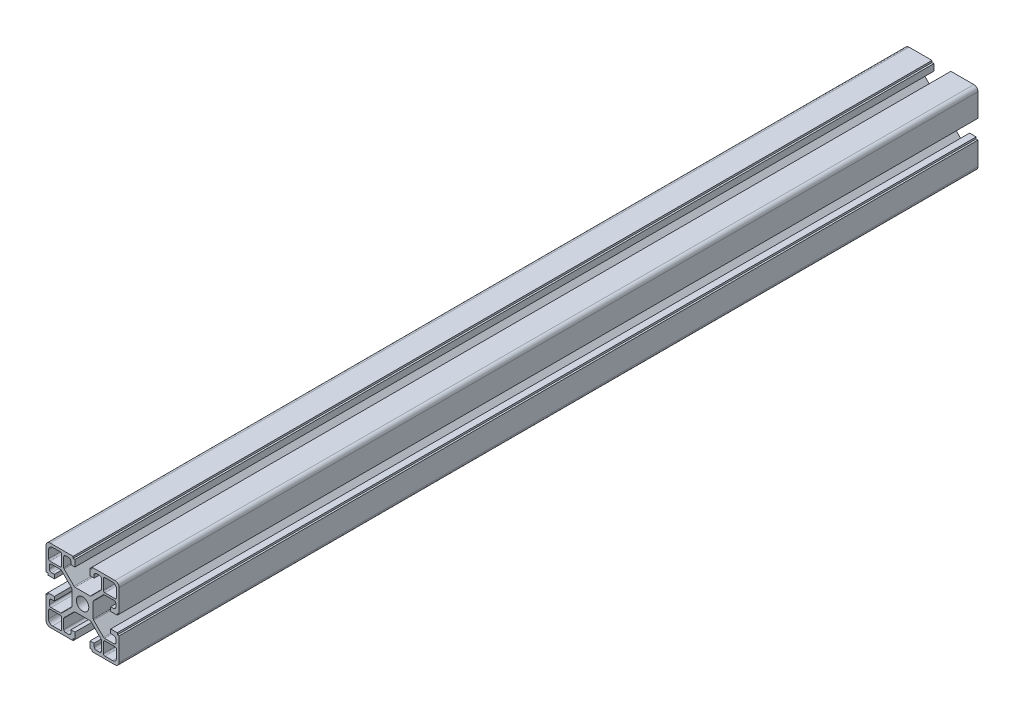
SolidWorks part; units mm, degrees
material "6063-T5"
ref_plane "Front Plane" through (0, 0, 0) normal (0, 0, 1) x (1, 0, 0)
ref_plane "Top Plane" through (0, 0, 0) normal (0, 1, 0) x (1, 0, 0)
ref_plane "Right Plane" through (0, 0, 0) normal (1, 0, 0) x (0, 0, -1)
sketch "Sketch1" plane through (0, 0, 0) normal (0, 0, 1) x (1, 0, 0)
  line L4 (20, 17.75) -> (20, 5.15)
  line L5 (0, -17.7813) -> (0, 18.2) construction
  line L6 (0, 0) -> (38.8613, 0) construction
  line L8 (18.6, 16.35) -> (18.6, 12.2)
  line L10 (11.4, 17.8) -> (11.4, 12.2)
  line L11 (-4.1, 5.85) -> (4.1, 5.85)
  line L14 (5.85, 4.1089) -> (5.85, -4.1089)
  line L17 (12.2, 11.4) -> (17.8, 11.4)
  line L24 (4.15, 19) -> (4.15, 15.4)
  line L25 (4.15, 15.4) -> (6.35, 15.4)
  line L26 (6.35, 15.4) -> (6.35, 16.95)
  line L27 (10.3, 17.2) -> (10.3, 12.0545)
  line L28 (10.0659, 11.489) -> (4.6659, 6.0845)
  line L29 (6.0841, 4.6743) -> (11.4708, 10.0655)
  line L30 (12.0367, 10.3) -> (17.2, 10.3)
  line L31 (18.2, 9.3) -> (18.2, 7.6)
  line L32 (16.95, 6.35) -> (15.4, 6.35)
  line L33 (15.4, 6.35) -> (15.4, 4.15)
  line L34 (15.4, 4.15) -> (19, 4.15)
  line L35 (18.6, 18.6) -> (18.6, -18.6) construction
  line L36 (-18.6, 18.6) -> (18.6, 18.6) construction
  line L37 (-20, 20) -> (20, 20) construction
  line L38 (20, 20) -> (20, -20) construction
  line L40 (7.6, 18.2) -> (9.3, 18.2)
  line L42 (4.15, 19) -> (5.15, 19)
  line L43 (5.15, 19) -> (5.15, 20)
  line L56 (-18.6, 18.6) -> (-18.6, -18.6) construction
  line L57 (-20, 20) -> (-20, -20) construction
  line L60 (5.15, 20) -> (17.75, 20)
  line L91 (-18.6, -18.6) -> (18.6, -18.6) construction
  line L92 (-20, -20) -> (20, -20) construction
  line L93 (12.2, 18.6) -> (16.35, 18.6)
  line L94 (17.9399, 17.9421) -> (20, 20) construction
  line L95 (0, 0) -> (11.4, 11.4094) construction
  line L101 (19, 4.15) -> (19, 5.15)
  line L102 (19, 5.15) -> (20, 5.15)
  line L104 (-5.85, 4.1089) -> (-5.85, -4.1089)
  line L105 (-19, 5.15) -> (-20, 5.15)
  line L106 (-19, 4.15) -> (-19, 5.15)
  line L107 (-12.2, 18.6) -> (-16.35, 18.6)
  line L108 (-5.15, 20) -> (-17.75, 20)
  line L109 (-5.15, 19) -> (-5.15, 20)
  line L110 (-4.15, 19) -> (-5.15, 19)
  line L111 (-7.6, 18.2) -> (-9.3, 18.2)
  line L112 (-15.4, 4.15) -> (-19, 4.15)
  line L113 (-15.4, 6.35) -> (-15.4, 4.15)
  line L114 (-16.95, 6.35) -> (-15.4, 6.35)
  line L115 (-18.2, 9.3) -> (-18.2, 7.6)
  line L116 (-12.0367, 10.3) -> (-17.2, 10.3)
  line L117 (-6.0841, 4.6743) -> (-11.4708, 10.0655)
  line L118 (-10.0659, 11.489) -> (-4.6659, 6.0845)
  line L119 (-10.3, 17.2) -> (-10.3, 12.0545)
  line L120 (-6.35, 15.4) -> (-6.35, 16.95)
  line L121 (-4.15, 15.4) -> (-6.35, 15.4)
  line L122 (-4.15, 19) -> (-4.15, 15.4)
  line L123 (-12.2, 11.4) -> (-17.8, 11.4)
  line L124 (-11.4, 17.8) -> (-11.4, 12.2)
  line L125 (-18.6, 16.35) -> (-18.6, 12.2)
  line L126 (-20, 17.75) -> (-20, 5.15)
  line L127 (-20, -17.75) -> (-20, -5.15)
  line L128 (-18.6, -16.35) -> (-18.6, -12.2)
  line L129 (-11.4, -17.8) -> (-11.4, -12.2)
  line L130 (-12.2, -11.4) -> (-17.8, -11.4)
  line L131 (-4.15, -19) -> (-4.15, -15.4)
  line L132 (-4.15, -15.4) -> (-6.35, -15.4)
  line L133 (-6.35, -15.4) -> (-6.35, -16.95)
  line L134 (-10.3, -17.2) -> (-10.3, -12.0545)
  line L135 (-10.0659, -11.489) -> (-4.6659, -6.0845)
  line L136 (-6.0841, -4.6743) -> (-11.4708, -10.0655)
  line L137 (-12.0367, -10.3) -> (-17.2, -10.3)
  line L138 (-18.2, -9.3) -> (-18.2, -7.6)
  line L139 (-16.95, -6.35) -> (-15.4, -6.35)
  line L140 (-15.4, -6.35) -> (-15.4, -4.15)
  line L141 (-15.4, -4.15) -> (-19, -4.15)
  line L142 (-7.6, -18.2) -> (-9.3, -18.2)
  line L143 (-4.15, -19) -> (-5.15, -19)
  line L144 (-5.15, -19) -> (-5.15, -20)
  line L145 (-5.15, -20) -> (-17.75, -20)
  line L146 (-12.2, -18.6) -> (-16.35, -18.6)
  line L147 (-19, -4.15) -> (-19, -5.15)
  line L148 (-19, -5.15) -> (-20, -5.15)
  line L149 (19, -5.15) -> (20, -5.15)
  line L150 (19, -4.15) -> (19, -5.15)
  line L151 (12.2, -18.6) -> (16.35, -18.6)
  line L152 (5.15, -20) -> (17.75, -20)
  line L153 (5.15, -19) -> (5.15, -20)
  line L154 (4.15, -19) -> (5.15, -19)
  line L155 (7.6, -18.2) -> (9.3, -18.2)
  line L156 (15.4, -4.15) -> (19, -4.15)
  line L157 (15.4, -6.35) -> (15.4, -4.15)
  line L158 (16.95, -6.35) -> (15.4, -6.35)
  line L159 (18.2, -9.3) -> (18.2, -7.6)
  line L160 (12.0367, -10.3) -> (17.2, -10.3)
  line L161 (6.0841, -4.6743) -> (11.4708, -10.0655)
  line L162 (10.0659, -11.489) -> (4.6659, -6.0845)
  line L163 (10.3, -17.2) -> (10.3, -12.0545)
  line L164 (6.35, -15.4) -> (6.35, -16.95)
  line L165 (4.15, -15.4) -> (6.35, -15.4)
  line L166 (4.15, -19) -> (4.15, -15.4)
  line L167 (12.2, -11.4) -> (17.8, -11.4)
  line L168 (-4.1, -5.85) -> (4.1, -5.85)
  line L169 (11.4, -17.8) -> (11.4, -12.2)
  line L170 (18.6, -16.35) -> (18.6, -12.2)
  line L171 (20, -17.75) -> (20, -5.15)
  circle A0 centre (0, 0) radius 3.4
  arc A7 (16.35, 18.6) -> (18.6, 16.35) centre (16.35, 16.35) cw
  arc A8 (20, 17.75) -> (17.75, 20) centre (17.75, 17.75) ccw
  arc A9 (6.35, 16.95) -> (7.6, 18.2) centre (7.6, 16.95) cw
  arc A10 (18.2, 7.6) -> (16.95, 6.35) centre (16.95, 7.6) cw
  arc A11 (17.2, 10.3) -> (18.2, 9.3) centre (17.2, 9.3) cw
  arc A12 (9.3, 18.2) -> (10.3, 17.2) centre (9.3, 17.2) cw
  arc A13 (4.6659, 6.0845) -> (4.1, 5.85) centre (4.1, 6.65) cw
  arc A14 (6.0841, 4.6743) -> (5.85, 4.1089) centre (6.65, 4.1089) ccw
  arc A15 (17.8, 11.4) -> (18.6, 12.2) centre (17.8, 12.2) ccw
  arc A16 (12.2, 18.6) -> (11.4, 17.8) centre (12.2, 17.8) ccw
  arc A17 (11.4, 12.2) -> (12.2, 11.4) centre (12.2, 12.2) ccw
  arc A18 (11.4708, 10.0655) -> (12.0367, 10.3) centre (12.0367, 9.5) cw
  arc A19 (10.3, 12.0545) -> (10.0659, 11.489) centre (9.5, 12.0545) cw
  arc A20 (-10.3, 12.0545) -> (-10.0659, 11.489) centre (-9.5, 12.0545) ccw
  arc A21 (-11.4708, 10.0655) -> (-12.0367, 10.3) centre (-12.0367, 9.5) ccw
  arc A22 (-11.4, 12.2) -> (-12.2, 11.4) centre (-12.2, 12.2) cw
  arc A23 (-12.2, 18.6) -> (-11.4, 17.8) centre (-12.2, 17.8) cw
  arc A24 (-17.8, 11.4) -> (-18.6, 12.2) centre (-17.8, 12.2) cw
  arc A25 (-6.0841, 4.6743) -> (-5.85, 4.1089) centre (-6.65, 4.1089) cw
  arc A26 (-4.6659, 6.0845) -> (-4.1, 5.85) centre (-4.1, 6.65) ccw
  arc A27 (-9.3, 18.2) -> (-10.3, 17.2) centre (-9.3, 17.2) ccw
  arc A28 (-17.2, 10.3) -> (-18.2, 9.3) centre (-17.2, 9.3) ccw
  arc A29 (-18.2, 7.6) -> (-16.95, 6.35) centre (-16.95, 7.6) ccw
  arc A30 (-6.35, 16.95) -> (-7.6, 18.2) centre (-7.6, 16.95) ccw
  arc A31 (-20, 17.75) -> (-17.75, 20) centre (-17.75, 17.75) cw
  arc A32 (-16.35, 18.6) -> (-18.6, 16.35) centre (-16.35, 16.35) ccw
  arc A33 (-16.35, -18.6) -> (-18.6, -16.35) centre (-16.35, -16.35) cw
  arc A34 (-20, -17.75) -> (-17.75, -20) centre (-17.75, -17.75) ccw
  arc A35 (-6.35, -16.95) -> (-7.6, -18.2) centre (-7.6, -16.95) cw
  arc A36 (-18.2, -7.6) -> (-16.95, -6.35) centre (-16.95, -7.6) cw
  arc A37 (-17.2, -10.3) -> (-18.2, -9.3) centre (-17.2, -9.3) cw
  arc A38 (-9.3, -18.2) -> (-10.3, -17.2) centre (-9.3, -17.2) cw
  arc A39 (-4.6659, -6.0845) -> (-4.1, -5.85) centre (-4.1, -6.65) cw
  arc A40 (-6.0841, -4.6743) -> (-5.85, -4.1089) centre (-6.65, -4.1089) ccw
  arc A41 (-17.8, -11.4) -> (-18.6, -12.2) centre (-17.8, -12.2) ccw
  arc A42 (-12.2, -18.6) -> (-11.4, -17.8) centre (-12.2, -17.8) ccw
  arc A43 (-11.4, -12.2) -> (-12.2, -11.4) centre (-12.2, -12.2) ccw
  arc A44 (-11.4708, -10.0655) -> (-12.0367, -10.3) centre (-12.0367, -9.5) cw
  arc A45 (-10.3, -12.0545) -> (-10.0659, -11.489) centre (-9.5, -12.0545) cw
  arc A46 (10.3, -12.0545) -> (10.0659, -11.489) centre (9.5, -12.0545) ccw
  arc A47 (11.4708, -10.0655) -> (12.0367, -10.3) centre (12.0367, -9.5) ccw
  arc A48 (11.4, -12.2) -> (12.2, -11.4) centre (12.2, -12.2) cw
  arc A49 (12.2, -18.6) -> (11.4, -17.8) centre (12.2, -17.8) cw
  arc A50 (17.8, -11.4) -> (18.6, -12.2) centre (17.8, -12.2) cw
  arc A51 (6.0841, -4.6743) -> (5.85, -4.1089) centre (6.65, -4.1089) cw
  arc A52 (4.6659, -6.0845) -> (4.1, -5.85) centre (4.1, -6.65) ccw
  arc A53 (9.3, -18.2) -> (10.3, -17.2) centre (9.3, -17.2) ccw
  arc A54 (17.2, -10.3) -> (18.2, -9.3) centre (17.2, -9.3) ccw
  arc A55 (18.2, -7.6) -> (16.95, -6.35) centre (16.95, -7.6) ccw
  arc A56 (6.35, -16.95) -> (7.6, -18.2) centre (7.6, -16.95) ccw
  arc A57 (20, -17.75) -> (17.75, -20) centre (17.75, -17.75) cw
  arc A58 (16.35, -18.6) -> (18.6, -16.35) centre (16.35, -16.35) ccw
  point P0 (0, 0)
  point P16 (-5.85, 0)
  point P66 (0, 5.85)
  point P120 (5.85, 0)
  point P218 (0, -5.85)
  dimension "D5" = 6.8
  dimension "D6" = 1.4
  dimension "D15" = 5.85
  dimension "D44" = 2.25
  dimension "D25" = 1.25
  dimension "D26" = 1
  dimension "D27" = 0.8
  dimension "D7" = 1.1
  dimension "D8" = 1.1
  dimension "D9" = 1.8
  dimension "D10" = 2.2
  dimension "D11" = 4.6
  dimension "D12" = 1.8
  dimension "D13" = 2.2
  dimension "D14" = 5.85
  dimension "D16" = 1.4
  dimension "D17" = 4.15
  dimension "D18" = 1
  dimension "D19" = 1
  dimension "D20" = 10.3
  dimension "D21" = 4.15
  dimension "D22" = 2
  dimension "D23" = 45.024
  dimension "D24" = 1
  dimension "D41" = 10.3
  dimension "D60" = 14.15
  dimension "D73" = 1
  dimension "D74" = 1
  dimension "D82" = 14.15
  dimension "D3" = 4.6
extrude "Boss-Extrude1" add sketch "Sketch1" along normal blind 713
sketch "Sketch2" plane through (0, 20, 0) normal (0, 1, 0) x (1, 0, 0)
  line L0 (-20, -713) -> (-20, 0) construction
  line L1 (-20, -470) -> (20, -470)
  line L2 (-20, -470) -> (-20, -713)
  line L3 (-20, -713) -> (20, -713)
  line L4 (20, -470) -> (20, -713)
  line L5 (-5.15, 0) -> (-17.75, 0) construction
  dimension "D1" = 470
extrude "Cut-Extrude1" cut sketch "Sketch2" against normal through all
